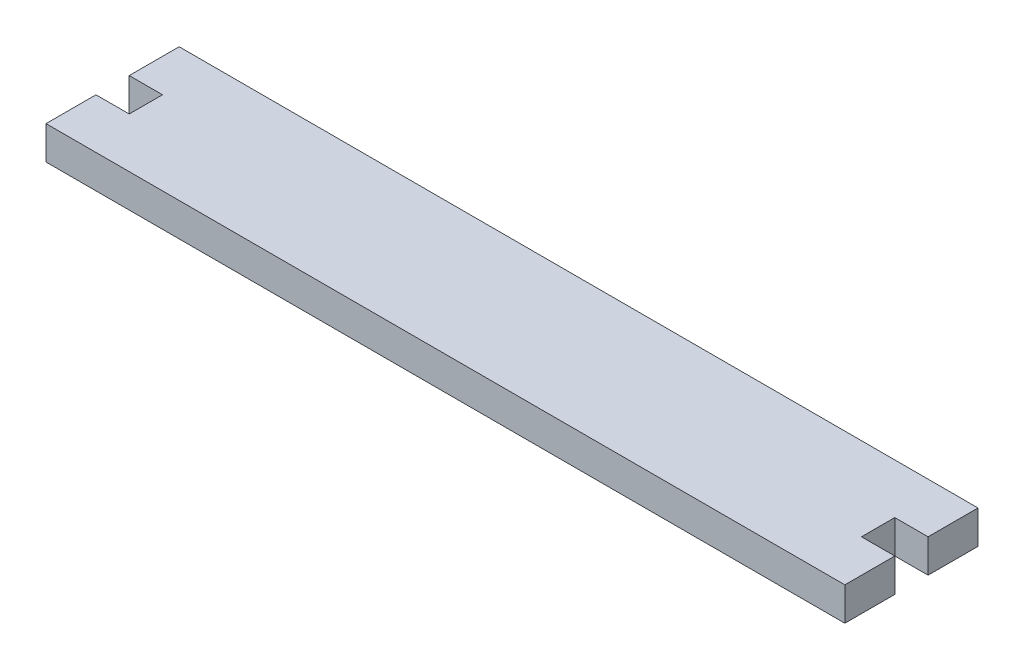
SolidWorks part; units mm, degrees
ref_plane "Front Plane" through (0, 0, 0) normal (0, 0, 1) x (1, 0, 0)
ref_plane "Top Plane" through (0, 0, 0) normal (0, 1, 0) x (1, 0, 0)
ref_plane "Right Plane" through (0, 0, 0) normal (1, 0, 0) x (0, 0, -1)
sketch "Sketch1" plane through (0, 0, 0) normal (0, 1, 0) x (1, 0, 0)
  line L0 (-38.1, 6.35) -> (-38.1, 1.5875)
  line L1 (38.1, -6.35) -> (-38.1, -6.35)
  line L2 (38.1, -6.35) -> (38.1, 6.35) construction
  line L3 (38.1, 6.35) -> (-38.1, 6.35)
  line L4 (-38.1, -6.35) -> (-38.1, 6.35) construction
  line L5 (38.1, -6.35) -> (-38.1, 6.35) construction
  line L6 (38.1, 6.35) -> (-38.1, -6.35) construction
  line L7 (-38.1, 1.5875) -> (-34.925, 1.5875)
  line L8 (-34.925, 1.5875) -> (-34.925, -1.5875)
  line L9 (-34.925, -1.5875) -> (-38.1, -1.5875)
  line L10 (-38.1, -1.5875) -> (-38.1, -6.35)
  line L11 (38.1, 6.35) -> (38.1, 1.5875)
  line L12 (38.1, 1.5875) -> (34.925, 1.5875)
  line L13 (34.925, 1.5875) -> (34.925, -1.5875)
  line L14 (34.925, -1.5875) -> (38.1, -1.5875)
  line L15 (38.1, -1.5875) -> (38.1, -6.35)
  point P0 (0, 0)
  point P15 (34.925, 0)
  dimension "D1" = 76.2
  dimension "D2" = 12.7
  dimension "D3" = 3.175
  dimension "D4" = 3.175
  dimension "D5" = 3.175
extrude "Boss-Extrude1" add sketch "Sketch1" along normal blind 3.175 contours L15 L1 L10 L9 L8 L7 L0 L3 L11 L12 L13 L14
sketch "Sketch2" plane through (0, 3.175, 0) normal (0, 1, 0) x (1, 0, 0)
  line L24 (38.1762, -6.4262) -> (38.1762, -1.5113)
  line L25 (38.1762, -1.5113) -> (35.0012, -1.5113)
  line L26 (35.0012, -1.5113) -> (35.0012, 1.5113)
  line L27 (35.0012, 1.5113) -> (38.1762, 1.5113)
  line L28 (38.1762, 1.5113) -> (38.1762, 6.4262)
  line L29 (-38.1762, -6.4262) -> (38.1762, -6.4262)
  line L30 (-38.1762, -1.5113) -> (-38.1762, -6.4262)
  line L31 (-35.0012, -1.5113) -> (-38.1762, -1.5113)
  line L32 (-35.0012, 1.5113) -> (-35.0012, -1.5113)
  line L33 (38.1762, 6.4262) -> (-38.1762, 6.4262)
  line L34 (-38.1762, 6.4262) -> (-38.1762, 1.5113)
  line L35 (-38.1762, 1.5113) -> (-35.0012, 1.5113)
  line L36 (38.1762, -6.4262) -> (38.1762, -1.5113)
  line L37 (38.1762, -1.5113) -> (35.0012, -1.5113)
  line L38 (35.0012, -1.5113) -> (35.0012, 1.5113)
  line L39 (35.0012, 1.5113) -> (38.1762, 1.5113)
  line L40 (38.1762, 1.5113) -> (38.1762, 6.4262)
  line L41 (-38.1762, -6.4262) -> (38.1762, -6.4262)
  line L42 (-38.1762, -1.5113) -> (-38.1762, -6.4262)
  line L43 (-35.0012, -1.5113) -> (-38.1762, -1.5113)
  line L44 (-35.0012, 1.5113) -> (-35.0012, -1.5113)
  line L45 (38.1762, 6.4262) -> (-38.1762, 6.4262)
  line L46 (-38.1762, 6.4262) -> (-38.1762, 1.5113)
  line L47 (-38.1762, 1.5113) -> (-35.0012, 1.5113)
  dimension "D1" = 0.0762
